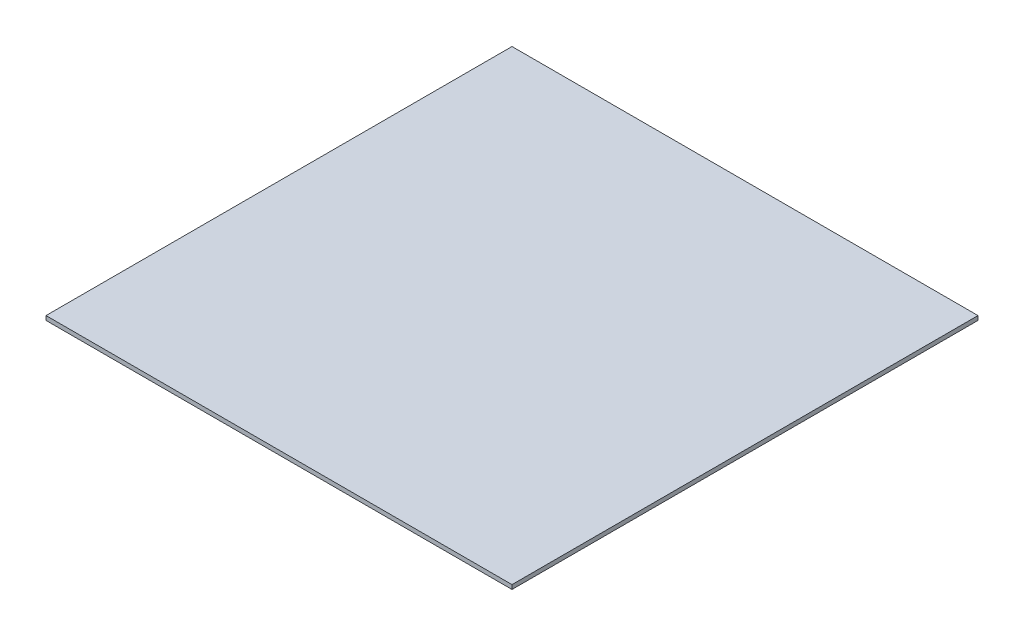
SolidWorks part; units mm, degrees
ref_plane "Front Plane" through (0, 0, 0) normal (0, 0, 1) x (1, 0, 0)
ref_plane "Top Plane" through (0, 0, 0) normal (0, 1, 0) x (1, 0, 0)
ref_plane "Right Plane" through (0, 0, 0) normal (1, 0, 0) x (0, 0, -1)
sketch "Sketch1" plane through (0, 0, 0) normal (0, 1, 0) x (1, 0, 0)
  line L1 (-139.7, -139.7) -> (139.7, -139.7)
  line L2 (-139.7, -139.7) -> (-139.7, 139.7)
  line L3 (-139.7, 139.7) -> (139.7, 139.7)
  line L4 (139.7, -139.7) -> (139.7, 139.7)
  line L5 (-139.7, -139.7) -> (139.7, 139.7) construction
  line L6 (-139.7, 139.7) -> (139.7, -139.7) construction
  point P0 (0, 0)
extrude "Boss-Extrude1" add sketch "Sketch1" along normal blind 2.54
